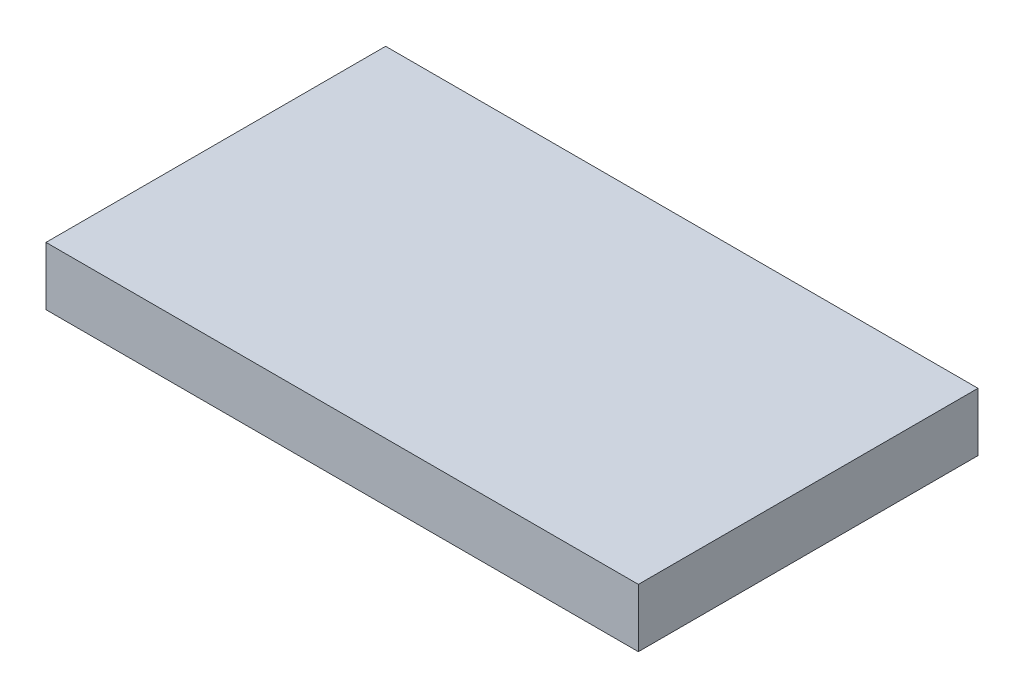
SolidWorks part; units mm, degrees
ref_plane "Спереди" through (0, 0, 0) normal (0, 0, 1) x (1, 0, 0)
ref_plane "Сверху" through (0, 0, 0) normal (0, 1, 0) x (1, 0, 0)
ref_plane "Справа" through (0, 0, 0) normal (1, 0, 0) x (0, 0, -1)
sketch "Матрица 5*3 первая кромка" plane through (0, 0, 0) normal (0, 1, 0) x (1, 0, 0)
  line L0 (0, 0) -> (368, 0) construction
  circle A0 centre (0, 0) radius 30
  circle A1 centre (92, 0) radius 30
  circle A2 centre (184, 0) radius 30
  circle A3 centre (276, 0) radius 30
  circle A4 centre (368, 0) radius 30
  circle A5 centre (0, -92) radius 30
  circle A6 centre (92, -92) radius 30
  circle A7 centre (184, -92) radius 30
  circle A8 centre (276, -92) radius 30
  circle A9 centre (368, -92) radius 30
  circle A10 centre (0, -184) radius 30
  circle A11 centre (92, -184) radius 30
  circle A12 centre (184, -184) radius 30
  circle A13 centre (276, -184) radius 30
  circle A14 centre (368, -184) radius 30
  dimension "D1" = 60
  dimension "D3" = 184
  dimension "D6" = 368
  dimension "D2" = 5
  dimension "D4" = 3
sketch "Габариты" plane through (0, 0, 0) normal (0, 1, 0) x (1, 0, 0)
  line L0 (443, 56.5) -> (-75, -240.5) construction
  line L1 (-75, 56.5) -> (443, 56.5)
  line L2 (-75, 56.5) -> (-75, -240.5)
  line L3 (-75, -240.5) -> (443, -240.5)
  line L4 (443, 56.5) -> (443, -240.5)
  line L5 (-75, 56.5) -> (443, -240.5) construction
  point P4 (184, -92)
  dimension "D1" = 297
  dimension "D2" = 518
extrude "Нижний наполнитель" add sketch "Габариты" along normal blind 51
extrude "Ложемент для КМЕ-11" cut sketch "Матрица 5*3 первая кромка" along normal blind 10
sketch "Матрица 5*3 вторая кромка" plane through (0, 0, 0) normal (0, -1, 0) x (1, 0, 0)
  circle A0 centre (0, 0) radius 22.5
  circle A1 centre (92, 0) radius 22.5
  circle A2 centre (184, 0) radius 22.5
  circle A3 centre (276, 0) radius 22.5
  circle A4 centre (368, 0) radius 22.5
  circle A5 centre (92, 92) radius 22.5
  circle A6 centre (184, 92) radius 22.5
  circle A7 centre (276, 92) radius 22.5
  circle A8 centre (368, 92) radius 22.5
  circle A9 centre (92, 184) radius 22.5
  circle A10 centre (184, 184) radius 22.5
  circle A11 centre (276, 184) radius 22.5
  circle A12 centre (368, 184) radius 22.5
  circle A13 centre (0, 92) radius 22.5
  circle A14 centre (0, 184) radius 22.5
  circle A15 centre (0, 0) radius 30 construction
  circle A16 centre (368, 0) radius 30 construction
  circle A18 centre (0, 184) radius 30 construction
  dimension "D3" = 45
  dimension "D1" = 5
  dimension "D2" = 3
extrude "Ложемент для КМЕ-11 (2)" cut sketch "Матрица 5*3 вторая кромка" against normal blind 25
